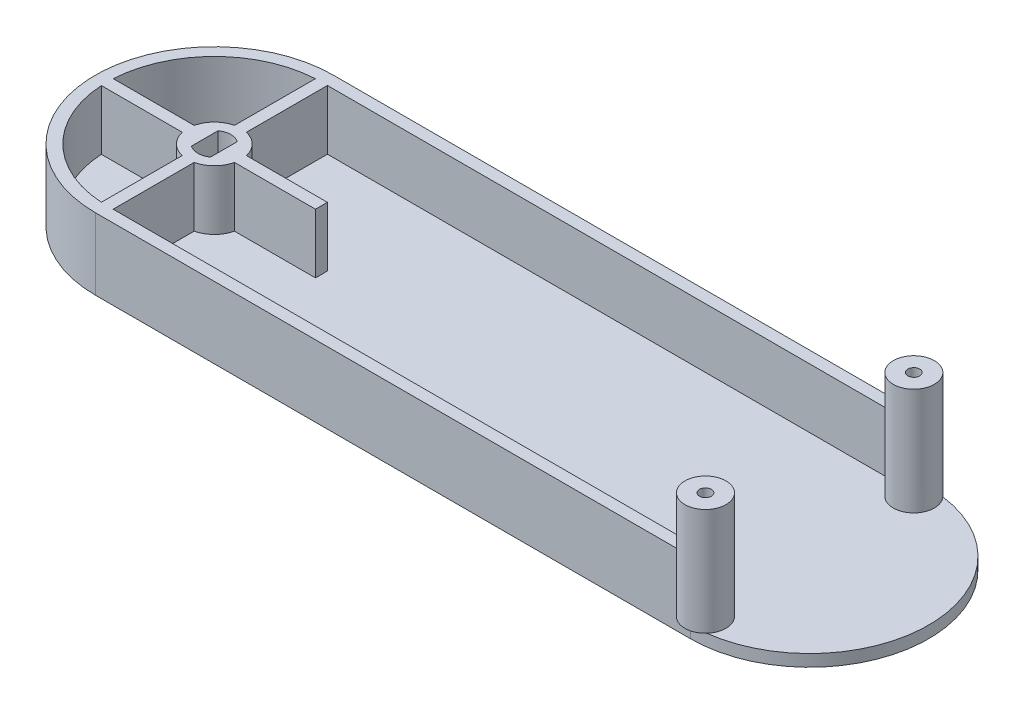
SolidWorks part; units mm, degrees
ref_plane "Front Plane" through (0, 0, 0) normal (0, 0, 1) x (1, 0, 0)
ref_plane "Top Plane" through (0, 0, 0) normal (0, 1, 0) x (1, 0, 0)
ref_plane "Right Plane" through (0, 0, 0) normal (1, 0, 0) x (0, 0, -1)
sketch "Sketch1" plane through (0, 0, 0) normal (0, 1, 0) x (1, 0, 0)
  line L0 (-50, 0) -> (50, 0) construction
  line L1 (-50, 20) -> (50, 20)
  line L2 (-50, -20) -> (50, -20)
  arc A0 (-50, 20) -> (-50, -20) centre (-50, 0) ccw
  arc A1 (50, -20) -> (50, 20) centre (50, 0) ccw
  point P2 (0, 0)
  dimension "D1" = 100
  dimension "D2" = 40
extrude "Boss-Extrude1" add sketch "Sketch1" along normal blind 12
shell "Shell1" thickness 2
sketch "Sketch3" plane through (0, 2, 0) normal (0, 1, 0) x (1, 0, 0)
  circle A0 centre (-50, 0) radius 2.75
  dimension "D1" = 5.5
extrude "Cut-Extrude1" cut sketch "Sketch3" against normal blind 2
sketch "Sketch4" plane through (0, 2, 0) normal (0, 1, 0) x (1, 0, 0)
  line L0 (-51.6, 2.2366) -> (-51.6, -2.2366)
  line L1 (-48.4, 2.2366) -> (-48.4, -2.2366)
  circle A0 centre (-50, 0) radius 4.5
  circle A1 centre (-50, 0) radius 2.75
  circle M3 centre (-50, 0) radius 2.75
  dimension "D1" = 5.5
  dimension "D2" = 9
  dimension "D3" = 3.2
  dimension "D4" = 1.6
extrude "Boss-Extrude2" add sketch "Sketch4" along normal blind 10 contours A0 M3 | L1 M3 | L0 M3
sketch "Sketch7" plane through (0, 2, 0) normal (0, 1, 0) x (1, 0, 0)
  line L0 (50, 18) -> (-50, 18) construction
  line L1 (-51, 4.2447) -> (-49, 4.2447)
  line L2 (-51, 4.2447) -> (-51, 18)
  line L3 (-51, 18) -> (-49, 18)
  line L4 (-49, 4.2447) -> (-49, 18)
  line L5 (-45.7553, 1) -> (-32, 1)
  line L6 (-45.7553, 1) -> (-45.7553, -1)
  line L7 (-45.7553, -1) -> (-32, -1)
  line L8 (-32, 1) -> (-32, -1)
  line L9 (-49, -4.2447) -> (-49, -18)
  line L10 (-49, -4.2447) -> (-51, -4.2447)
  line L11 (-51, -4.2447) -> (-51, -18)
  line L12 (-49, -18) -> (-51, -18)
  line L13 (-54.2447, -1) -> (-68, -1)
  line L14 (-54.2447, -1) -> (-54.2447, 1)
  line L15 (-54.2447, 1) -> (-68, 1)
  line L16 (-68, -1) -> (-68, 1)
  circle A3 centre (-50, 0) radius 4.3609
  circle A4 centre (-50, 0) radius 18
  point P13 (-50, 4.2447)
  point P29 (-50, 0)
  circle M8 centre (-50, 0) radius 4.5
  arc M9 (-50, 18) -> (-50, -18) centre (-50, 0) ccw
  line M10 (-50, -18) -> (50, -18)
  line M12 (50, 18) -> (-50, 18)
  dimension "D1" = 2
  dimension "D2" = 4
extrude "Boss-Extrude7" add sketch "Sketch7" along normal blind 10 contours L4 A4 L2 M9 M8 | L3 L2 M9 | A4 L4 M12 | L7 A4 L5 M8 | A4 L9 L11 M9 M8 | A4 L9 M10 | L15 L13 M8 M9
sketch "Sketch10" plane through (0, 12, 0) normal (0, 1, 0) x (1, 0, 0)
  line L1 (50, 20) -> (70, 20)
  line L2 (50, 20) -> (50, -20)
  line L3 (50, -20) -> (70, -20)
  line L4 (70, 20) -> (70, -20)
  dimension "D1" = 20
  dimension "D2" = 40
extrude "Cut-Extrude3" cut sketch "Sketch10" against normal up to surface (10 mm away) up to face at (-23.2276, 2, 0)
sketch "Sketch9" plane through (0, 2, 0) normal (0, 1, 0) x (1, 0, 0)
  line L11 (29.1415, 0) -> (74.619, 0) construction
  circle A11 centre (50, 0) radius 13.5
  circle A12 centre (50, -17.5) radius 1
  circle A13 centre (50, -17.5) radius 3.45
  circle A14 centre (50, 17.5) radius 3.45
  circle A15 centre (50, 17.5) radius 1
  point P10 (50, 0)
  point P11 (51.1184, -17.4642)
  dimension "D1" = 27
  dimension "D2" = 2
  dimension "D3" = 6.9
  dimension "D4" = 17.5
extrude "Boss-Extrude9" add sketch "Sketch9" along normal blind 18 contours A14 | A13 | A12 | A15
sketch "Sketch11" plane through (0, 12, 0) normal (0, 1, 0) x (1, 0, 0)
  circle A0 centre (50, 17.5) radius 1
  circle A1 centre (50, -17.5) radius 1
  dimension "D1" = 2
  dimension "D2" = 2
extrude "Cut-Extrude4" cut sketch "Sketch11" against normal up to surface (10 mm away) up to face at (-10.9711, 2, 0)
